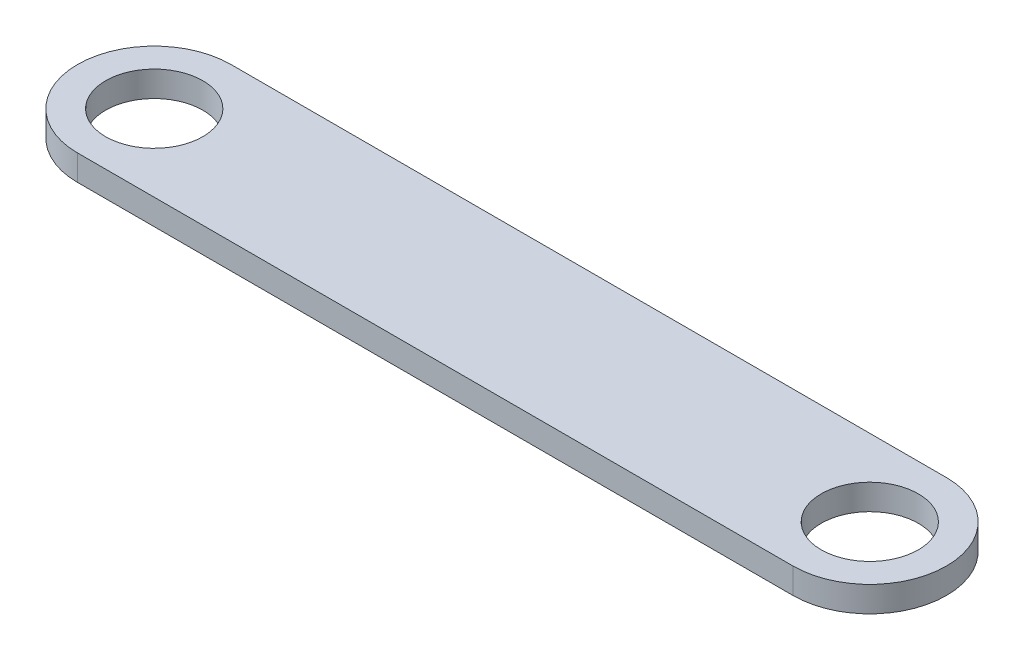
SolidWorks part; units mm, degrees
ref_plane "Alzado" through (0, 0, 0) normal (0, 0, 1) x (1, 0, 0)
ref_plane "Planta" through (0, 0, 0) normal (0, 1, 0) x (1, 0, 0)
ref_plane "Vista lateral" through (0, 0, 0) normal (1, 0, 0) x (0, 0, -1)
sketch "Croquis1" plane through (0, 0, 0) normal (0, 1, 0) x (1, 0, 0)
  line L0 (-35, 0) -> (35, 0) construction
  line L3 (-35, 7.5) -> (35, 7.5)
  line L4 (-35, -7.5) -> (35, -7.5)
  arc A2 (-35, 7.5) -> (-35, -7.5) centre (-35, 0) ccw
  arc A3 (35, -7.5) -> (35, 7.5) centre (35, 0) ccw
  point P2 (0, 0)
  dimension "D1" = 70
  dimension "D2" = 15
extrude "Saliente-Extruir1" add sketch "Croquis1" along normal blind 2.5
sketch "Croquis2" plane through (0, 2.5, 0) normal (0, 1, 0) x (1, 0, 0)
  circle A0 centre (-35, 0) radius 4.75
  circle A1 centre (35, 0) radius 4.75
  dimension "D1" = 9.5
extrude "Cortar-Extruir1" cut sketch "Croquis2" against normal through all
